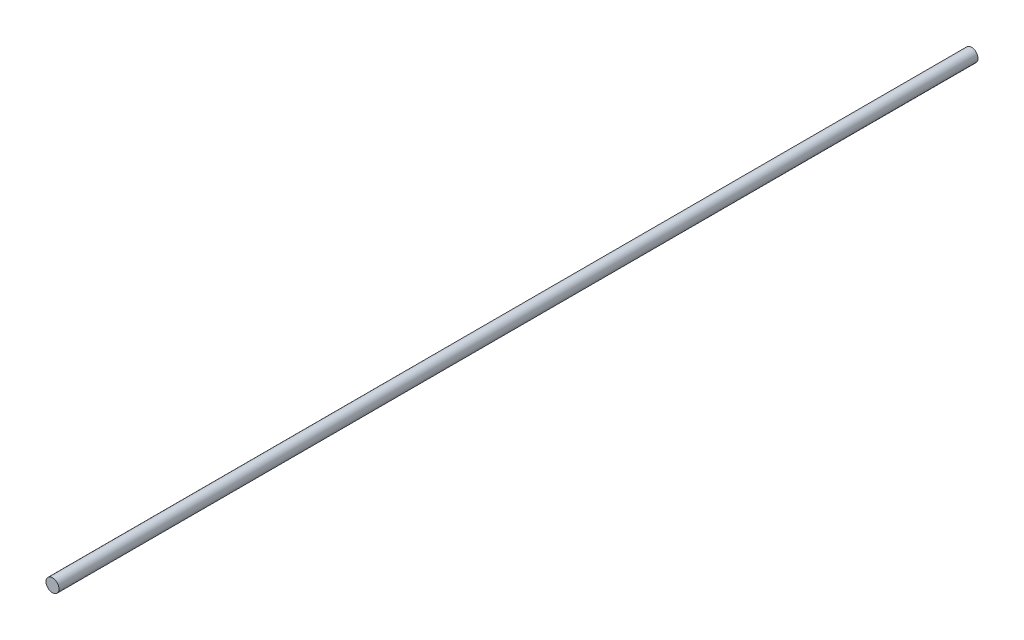
SolidWorks part; units mm, degrees
ref_plane "Front Plane" through (0, 0, 0) normal (0, 0, 1) x (1, 0, 0)
ref_plane "Top Plane" through (0, 0, 0) normal (0, 1, 0) x (1, 0, 0)
ref_plane "Right Plane" through (0, 0, 0) normal (1, 0, 0) x (0, 0, -1)
sketch "Sketch1" plane through (0, 0, 0) normal (0, 0, 1) x (1, 0, 0)
  circle A0 centre (0, 0) radius 12.5
extrude "Boss-Extrude1" add sketch "Sketch1" along normal blind 1770
